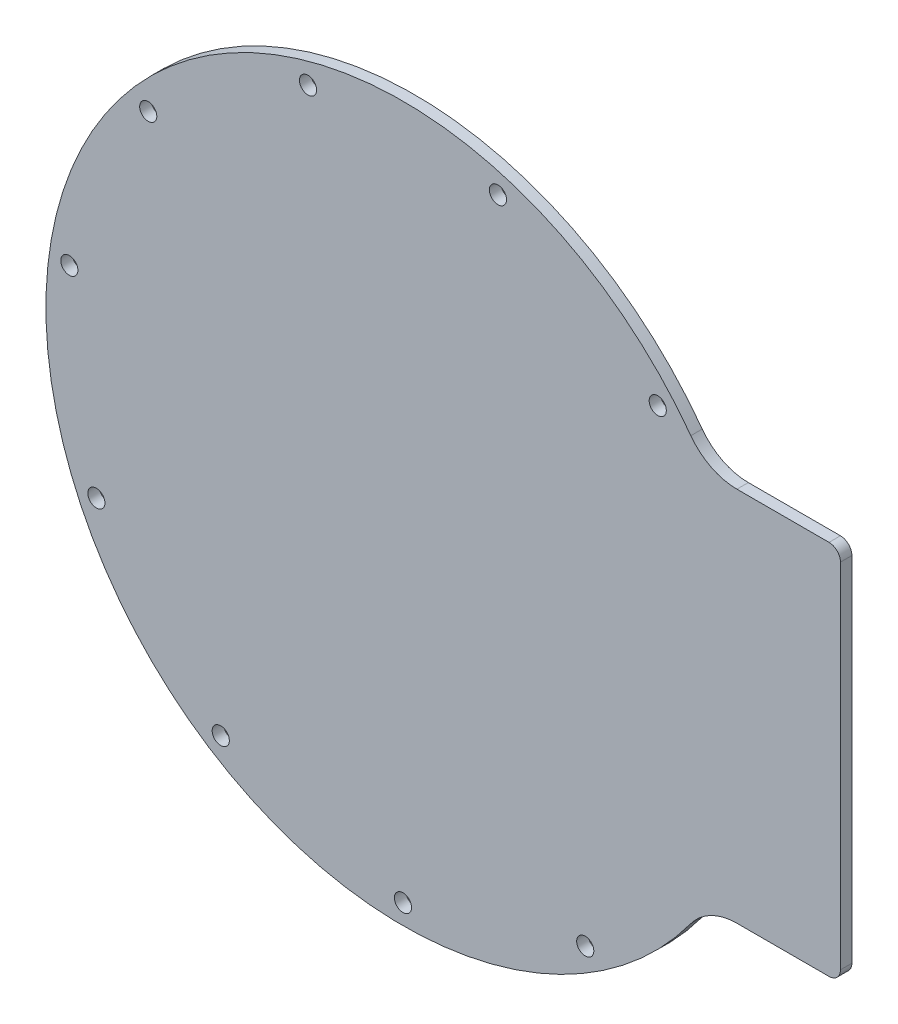
SolidWorks part; units mm, degrees
ref_plane "前视基准面" through (0, 0, 0) normal (0, 0, 1) x (1, 0, 0)
ref_plane "上视基准面" through (0, 0, 0) normal (0, 1, 0) x (1, 0, 0)
ref_plane "右视基准面" through (0, 0, 0) normal (1, 0, 0) x (0, 0, -1)
sketch "草图1" plane through (0, 0, 0) normal (0, 0, 1) x (1, 0, 0)
  line L2 (0, 0) -> (-102.4397, 0) construction
  line L3 (0, 1.2542) -> (0, 77.8801) construction
  line L4 (0, 0) -> (118.6635, 0) construction
  line L5 (0, 0) -> (0, -124.4057) construction
  line L32 (64.5685, 25.9) -> (64.5685, -25.9) construction
  line L45 (58.4452, 32.9) -> (74.5685, 32.9)
  line L46 (58.4452, -32.9) -> (74.5685, -32.9)
  line L47 (76.5685, -30.9) -> (76.5685, 30.9)
  circle A0 centre (0, 0) radius 59 construction
  circle A2 centre (0, 0) radius 62.5 construction
  circle A4 centre (0, -59) radius 1.5
  circle A8 centre (-31.8978, -49.634) radius 1.5
  circle A9 centre (-53.6683, -24.5095) radius 1.5
  circle A10 centre (-58.3995, 8.3966) radius 1.5
  circle A11 centre (-44.5892, 38.6368) radius 1.5
  circle A12 centre (-16.6222, 56.6101) radius 1.5
  circle A13 centre (16.6222, 56.6101) radius 1.5
  circle A14 centre (44.5892, 38.6368) radius 1.5
  circle A17 centre (31.8978, -49.634) radius 1.5
  circle A25 centre (0, 0) radius 50 construction
  arc A76 (50.3838, 36.9828) -> (50.3838, -36.9828) centre (0, 0) ccw
  arc A77 (58.4452, 32.9) -> (50.3838, 36.9828) centre (58.4452, 42.9) cw
  arc A78 (58.4452, -32.9) -> (50.3838, -36.9828) centre (58.4452, -42.9) ccw
  arc A85 (74.5685, -32.9) -> (76.5685, -30.9) centre (74.5685, -30.9) ccw
  arc A86 (74.5685, 32.9) -> (76.5685, 30.9) centre (74.5685, 30.9) cw
  circle A91 centre (53.6683, -24.5095) radius 1.5 construction
  circle A92 centre (58.3995, 8.3966) radius 1.5 construction
  point P164 (53.1398, 32.9)
  point P166 (53.1398, -32.9)
  dimension "D1" = 125
  dimension "D2" = 118
  dimension "D5" = 3
  dimension "D15" = 100
  dimension "D31" = 12
  dimension "D25" = 51.8
  dimension "D7" = 11
extrude "凸台-拉伸1" add sketch "草图1" along normal blind 2 contours A2
